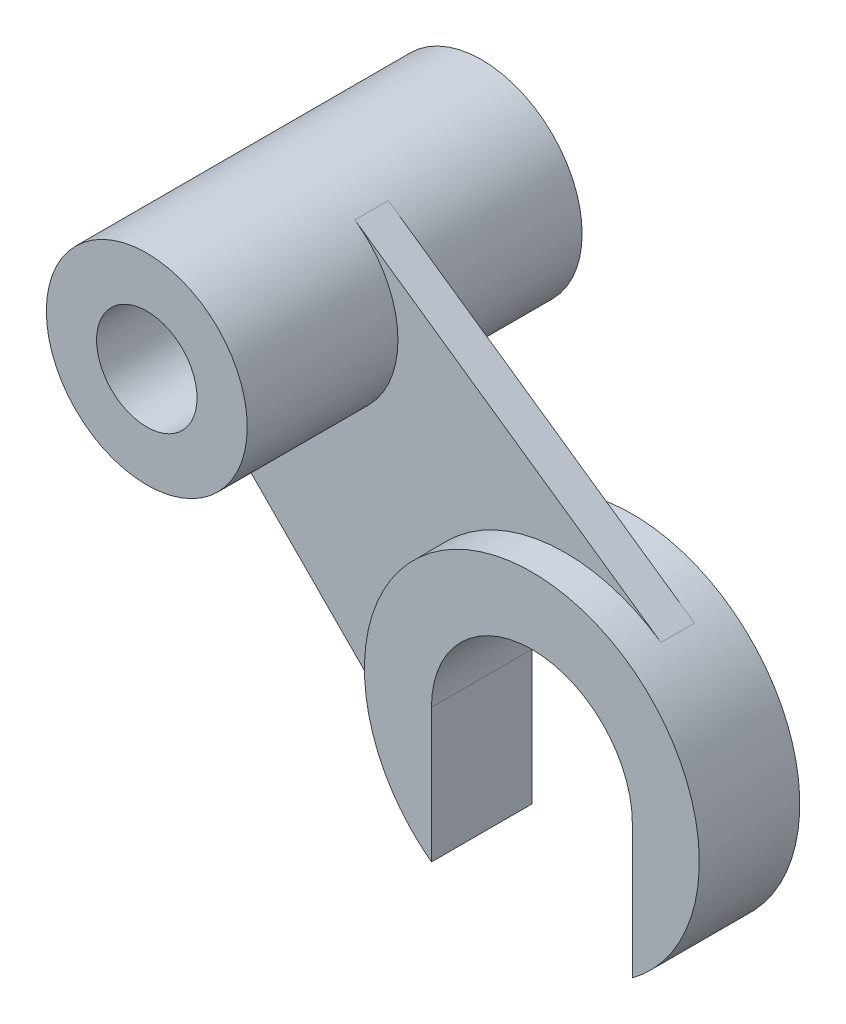
SolidWorks part; units mm, degrees
ref_plane "Front Plane" through (0, 0, 0) normal (0, 0, 1) x (1, 0, 0)
ref_plane "Top Plane" through (0, 0, 0) normal (0, 1, 0) x (1, 0, 0)
ref_plane "Right Plane" through (0, 0, 0) normal (1, 0, 0) x (0, 0, -1)
sketch "Sketch1" plane through (0, 0, 0) normal (0, 0, 1) x (1, 0, 0)
  circle A0 centre (0, 0) radius 30
  dimension "D1" = 60
extrude "Boss-Extrude1" add sketch "Sketch1" along normal mid plane 100
sketch "Sketch2" plane through (0, 0, 0) normal (0, 0, 1) x (1, 0, 0)
  circle A0 centre (80, -80) radius 50
  point P2 (0, 0)
  dimension "D1" = 100
  dimension "D2" = 80
  dimension "D3" = 80
extrude "Boss-Extrude2" add sketch "Sketch2" along normal mid plane 30 separate body
sketch "Sketch3" plane through (0, 0, 0) normal (0, 0, 1) x (1, 0, 0)
  line L0 (17.1291, 24.6291) -> (108.5485, -38.9515)
  line L1 (108.5485, -38.9515) -> (44.4774, -115.1872)
  line L2 (44.4774, -115.1872) -> (-30, -40)
  line L4 (-30, -40) -> (-30, 0)
  line L5 (-30, 0) -> (17.1291, 24.6291)
  circle A0 centre (0, 0) radius 30 construction
  circle A1 centre (80, -80) radius 50 construction
  point P4 (0, 0)
  point P9 (46.6321, -117.2368)
  point P10 (0, 0)
  point P11 (0, 0)
  point P12 (0, 0)
  dimension "D1" = 40
extrude "Boss-Extrude3" add sketch "Sketch3" along normal mid plane 10
sketch "Sketch4" plane through (0, 0, 15) normal (0, 0, 1) x (1, 0, 0)
  line L0 (80, -80) -> (80, -155.2726) construction
  line L1 (110, -80) -> (110, -155.2726)
  line L2 (50, -80) -> (50, -155.2726)
  arc A0 (110, -80) -> (50, -80) centre (80, -80) ccw
  arc A1 (50, -155.2726) -> (110, -155.2726) centre (80, -155.2726) ccw
  point P3 (80, -117.6363)
  dimension "D1" = 30
extrude "Cut-Extrude1" cut sketch "Sketch4" against normal through all
hole_wizard "Ø1.0mm Dowel Hole1" positions "Sketch5" profile "Sketch6" hole size "Ø1.0" standard "ISO" end condition through all
sketch "Sketch5" plane through (0, 0, 50) normal (0, 0, 1) x (1, 0, 0)
  point P0 (0, 0)
sketch "Sketch6" plane through (0, 0, 50) normal (1, 0, 0) x (0, -1, 0)
  line L0 (0, 0) -> (0, 100)
  line L1 (0, 100) -> (15, 100)
  line L2 (15, 100) -> (15, 0)
  line L5 (15, 0) -> (0, 0)
  line L11 (0, -6.35) -> (0, 107.95) construction
  dimension "Thru Hole Dia." = 30
  dimension "Thru Hole Depth" = 100
